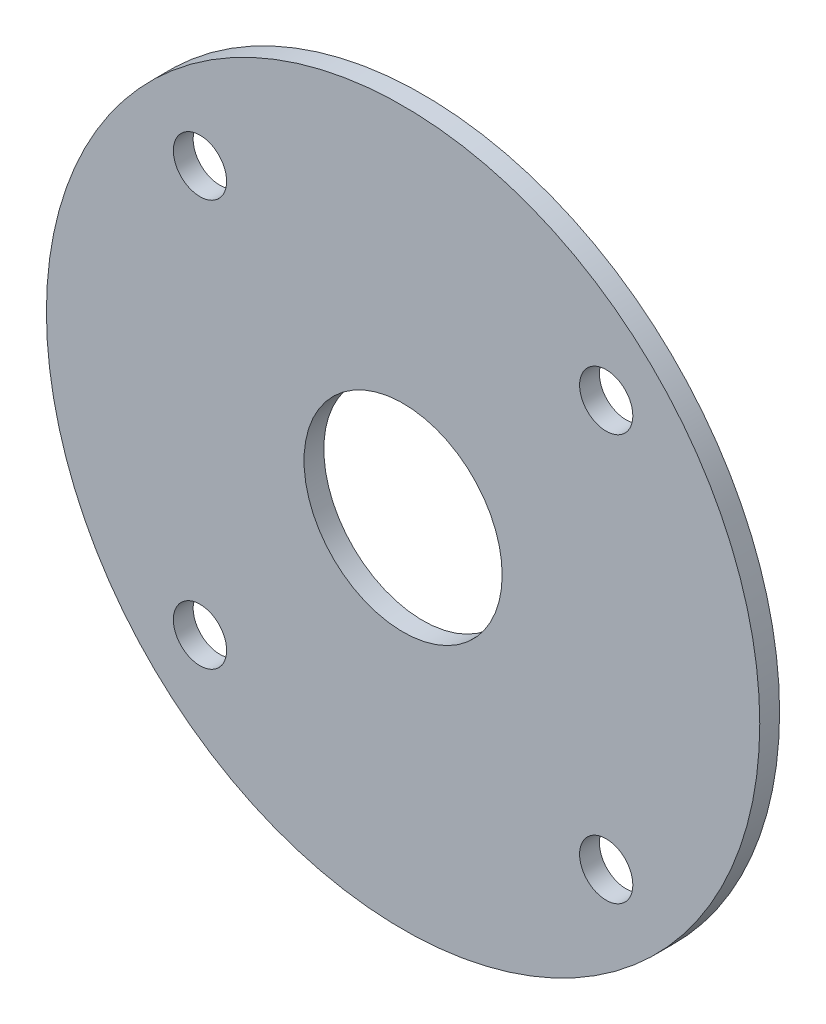
SolidWorks part; units mm, degrees
ref_plane "Front Plane" through (0, 0, 0) normal (0, 0, 1) x (1, 0, 0)
ref_plane "Top Plane" through (0, 0, 0) normal (0, 1, 0) x (1, 0, 0)
ref_plane "Right Plane" through (0, 0, 0) normal (1, 0, 0) x (0, 0, -1)
sketch "Sketch2" plane through (0, 0, 0) normal (0, 0, 1) x (1, 0, 0)
  circle A0 centre (0, 0) radius 114.3
  circle A1 centre (0, 0) radius 31.75
  dimension "D1" = 228.6
  dimension "D2" = 63.5
extrude "Extrude1" add sketch "Sketch2" along normal blind 6.35
sketch "Sketch3" plane through (0, 0, 6.35) normal (0, 0, 1) x (1, 0, 0)
  circle A0 centre (-65.0875, -65.0875) radius 8.5328
  circle A1 centre (-65.0875, 65.0875) radius 8.5328
  circle A2 centre (65.0875, 65.0875) radius 8.5328
  circle A3 centre (65.0875, -65.0875) radius 8.5328
  circle A4 centre (65.0875, -65.0875) radius 8.5328 construction
  circle A5 centre (-65.0875, -65.0875) radius 8.5328 construction
  circle A6 centre (-65.0875, 65.0875) radius 8.5328 construction
  circle A7 centre (65.0875, 65.0875) radius 8.5328 construction
extrude "Cut-Extrude1" cut sketch "Sketch3" against normal up to next
